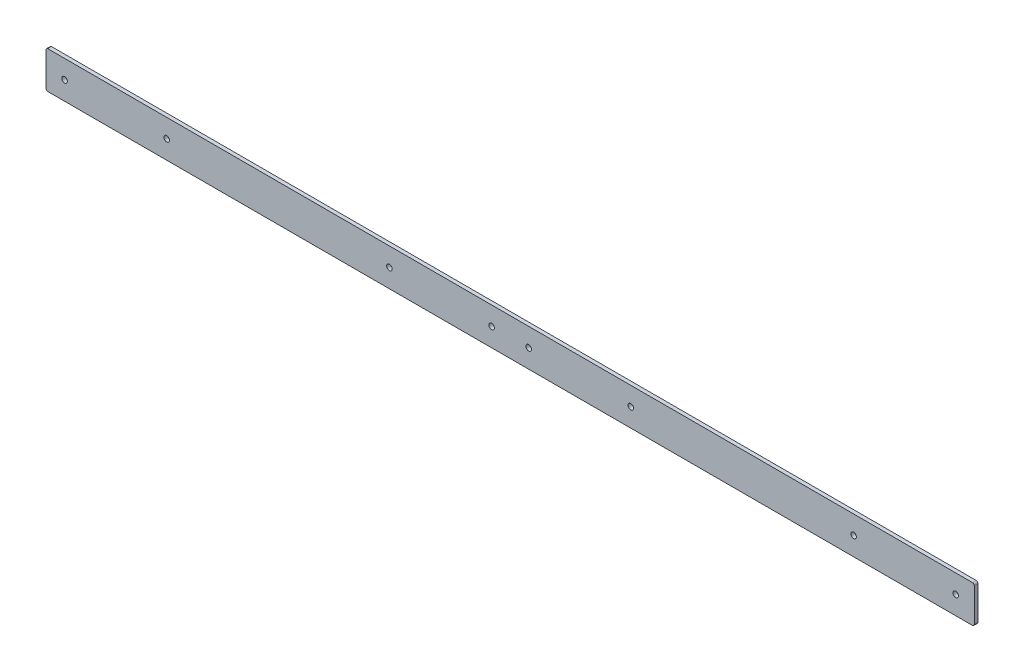
SolidWorks part; units mm, degrees
ref_plane "前视基准面" through (0, 0, 0) normal (0, 0, 1) x (1, 0, 0)
ref_plane "上视基准面" through (0, 0, 0) normal (0, 1, 0) x (1, 0, 0)
ref_plane "右视基准面" through (0, 0, 0) normal (1, 0, 0) x (0, 0, -1)
sketch "草图1" plane through (0, 0, 0) normal (0, 0, 1) x (1, 0, 0)
  line L0 (0, 0) -> (183.3198, 0) construction
  line L1 (-250, -10) -> (250, -10)
  line L2 (-250, -10) -> (-250, 10)
  line L3 (-250, 10) -> (250, 10)
  line L4 (250, -10) -> (250, 10)
  line L5 (-250, -10) -> (250, 10) construction
  line L6 (-250, 10) -> (250, -10) construction
  line L7 (0, 0) -> (0, -21.6711) construction
  circle A0 centre (240, 0) radius 1.5
  circle A1 centre (185, 0) radius 1.5
  circle A2 centre (-240, 0) radius 1.5
  circle A3 centre (-185, 0) radius 1.5
  circle A4 centre (-10, 0) radius 1.5
  circle A5 centre (-65, 0) radius 1.5
  circle A6 centre (10, 0) radius 1.5
  circle A7 centre (65, 0) radius 1.5
  point P0 (0, 0)
  point P16 (-250, 0)
  dimension "D3" = 3
  dimension "D8" = 10
  dimension "D1" = 20
  dimension "D2" = 500
  dimension "D4" = 55
  dimension "D5" = 55
  dimension "D6" = 10
  dimension "D7" = 10
  dimension "D9" = 55
extrude "凸台-拉伸1" add sketch "草图1" along normal blind 2
fillet "圆角1" radius 1 4 edges at (250, -10, 1) (250, 10, 1) (-250, -10, 1) (-250, 10, 1)
